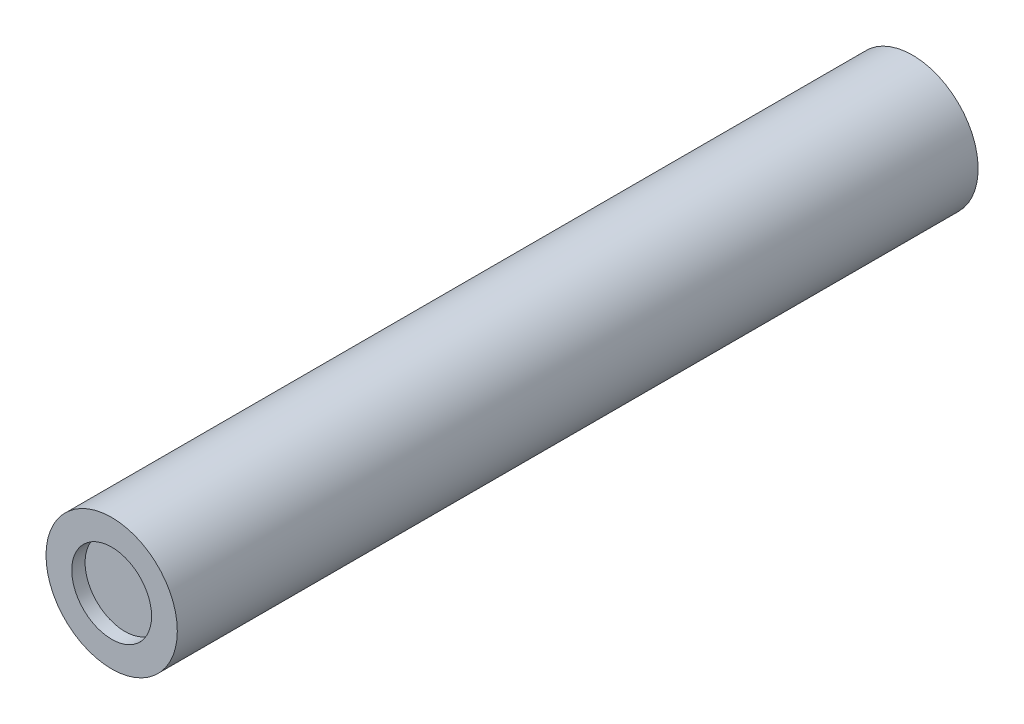
SolidWorks part; units mm, degrees
ref_plane "Front Plane" through (0, 0, 0) normal (0, 0, 1) x (1, 0, 0)
ref_plane "Top Plane" through (0, 0, 0) normal (0, 1, 0) x (1, 0, 0)
ref_plane "Right Plane" through (0, 0, 0) normal (1, 0, 0) x (0, 0, -1)
sketch "Sketch1" plane through (0, 0, 0) normal (0, 0, 1) x (1, 0, 0)
  circle A0 centre (0, 0) radius 12.5
  dimension "D1" = 25
extrude "Boss-Extrude1" add sketch "Sketch1" along normal blind 155
sketch "Sketch2" plane through (0, 0, 0) normal (0, 0, -1) x (-1, 0, 0)
  circle A0 centre (0, 0) radius 15.0994
extrude "Cut-Extrude1" cut sketch "Sketch2" against normal blind 2.54 contours A0
sketch "Sketch3" plane through (0, 0, 155) normal (0, 0, 1) x (1, 0, 0)
  circle A0 centre (0, 0) radius 7.6
extrude "Cut-Extrude2" cut sketch "Sketch3" against normal blind 2.54
